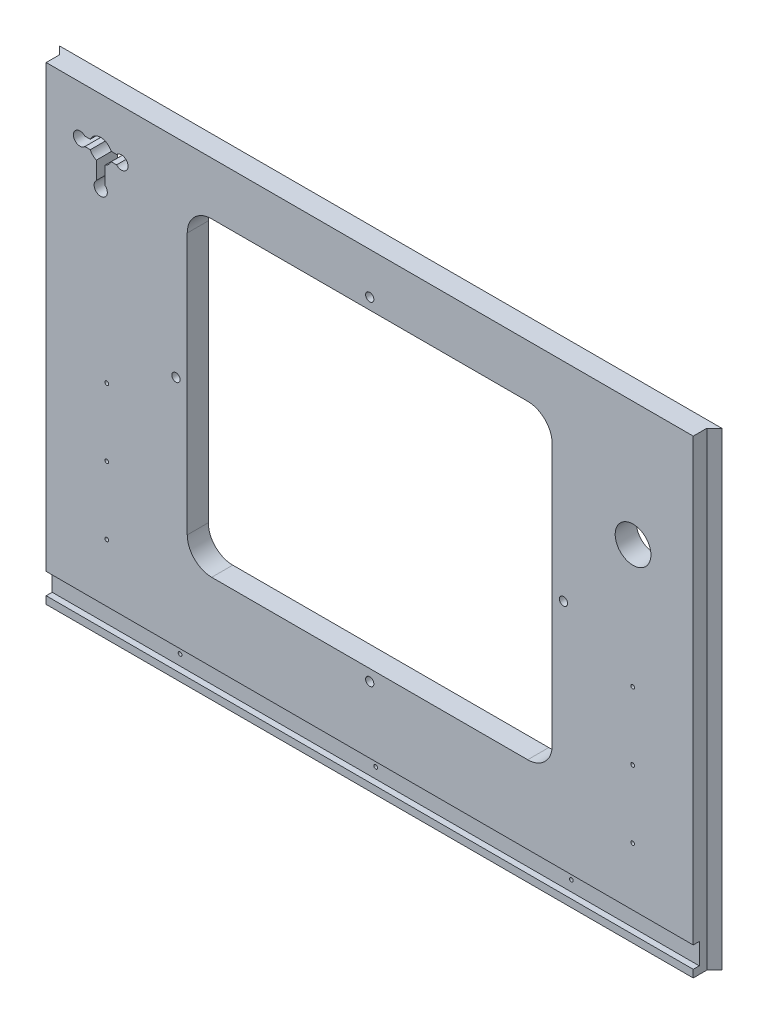
SolidWorks part; units mm, degrees
material "Pine"
ref_plane "Front Plane" through (0, 0, 0) normal (0, 0, 1) x (1, 0, 0)
ref_plane "Top Plane" through (0, 0, 0) normal (0, 1, 0) x (1, 0, 0)
ref_plane "Right Plane" through (0, 0, 0) normal (1, 0, 0) x (0, 0, -1)
sketch "Sketch1" plane through (0, 0, 0) normal (0, 0, 1) x (1, 0, 0)
  line L0 (8932.6508, -5243.5125) -> (10226.1458, -5243.5125)
  line L1 (9086.3208, -4722.0918) -> (10222.9708, -4853.7812)
  line L2 (8914.8708, -6342.0625) -> (10197.5708, -6342.0625)
  line L3 (8914.8708, -5808.6625) -> (10197.5708, -5808.6625)
  line L4 (8919.6333, -5253.0375) -> (10218.2083, -5253.0375)
  line L5 (9134.2633, -4656.1375) -> (9134.2633, -4638.3575)
  line L6 (9091.0833, -4638.3575) -> (9134.2633, -4638.3575)
  line L7 (9091.0833, -4567.2375) -> (9091.0833, -4638.3575)
  line L8 (9134.2633, -4656.1375) -> (9581.3033, -4656.1375)
  line L9 (9091.0833, -4567.2375) -> (9624.4833, -4567.2375)
  line L10 (9581.3033, -4656.1375) -> (9581.3033, -4638.3575)
  line L11 (9581.3033, -4638.3575) -> (9624.4833, -4638.3575)
  line L12 (9624.4833, -4567.2375) -> (9624.4833, -4638.3575)
  line L13 (8932.6508, -5225.7325) -> (9344.9775, -5225.7325)
  line L14 (8932.6508, -5256.2125) -> (8932.6508, -5243.5125)
  line L15 (8911.6958, -5256.2125) -> (8932.6508, -5256.2125)
  line L16 (8914.8708, -4722.0918) -> (9086.3208, -4722.0918)
  line L17 (8911.6958, -4715.5913) -> (8932.6508, -4715.5913)
  line L18 (8914.8708, -6342.0625) -> (8914.8708, -5808.6625)
  line L19 (12082.9917, -4722.0918) -> (10946.3417, -4853.7812)
  line L20 (12236.6617, -5243.5125) -> (10943.1667, -5243.5125)
  line L21 (10951.1042, -5253.0375) -> (12249.6792, -5253.0375)
  line L22 (10838.3917, -5656.2625) -> (11308.2917, -5656.2625)
  line L23 (10838.3917, -5719.7625) -> (11308.2917, -5719.7625)
  line L24 (10838.3917, -5742.5368) -> (11308.2917, -5742.5368)
  line L25 (10806.6417, -6342.0625) -> (11340.0417, -6342.0625)
  line L26 (10803.4667, -6335.7125) -> (11343.2167, -6335.7125)
  line L27 (10803.4667, -6317.9325) -> (11343.2167, -6317.9325)
  line L28 (10943.1667, -5225.7325) -> (11376.4483, -5225.7325)
  line L29 (11506.7292, -4754.5625) -> (10806.6417, -4827.5875)
  line L30 (11506.7292, -4567.2375) -> (11506.7292, -4754.5625)
  line L31 (10806.6417, -4567.2375) -> (10806.6417, -4827.5875)
  line L32 (10806.6417, -4567.2375) -> (11506.7292, -4567.2375)
  line L33 (10235.6708, -6329.3625) -> (10245.1958, -6329.3625)
  line L34 (10245.1958, -6329.3625) -> (10254.7208, -6278.5625)
  line L35 (10302.3458, -6329.3625) -> (10311.8708, -6278.5625)
  line L36 (10302.3458, -6329.3625) -> (10292.8208, -6329.3625)
  line L37 (10245.1958, -5821.3625) -> (10254.7208, -5872.1625)
  line L38 (10235.6708, -5821.3625) -> (10245.1958, -5821.3625)
  line L39 (10292.8208, -5821.3625) -> (10302.3458, -5821.3625)
  line L40 (10302.3458, -5821.3625) -> (10311.8708, -5872.1625)
  line L41 (10235.6708, -5821.3625) -> (10235.6708, -6329.3625)
  line L42 (10254.7208, -5872.1625) -> (10254.7208, -6278.5625)
  line L43 (10311.8708, -5872.1625) -> (10311.8708, -6278.5625)
  line L44 (10292.8208, -5821.3625) -> (10292.8208, -6329.3625)
  line L45 (8932.6508, -5225.7325) -> (8932.6508, -4715.5913)
  line L46 (8911.6958, -4715.5913) -> (8911.6958, -5256.2125)
  line L47 (8914.8708, -5248.275) -> (8914.8708, -4722.0918)
  line L48 (8919.6333, -5253.0375) -> (8914.8708, -5248.275)
  line L49 (8914.8708, -5145.0875) -> (8937.426, -5145.0875)
  line L50 (8914.8708, -5202.2375) -> (8937.426, -5202.2375)
  line L51 (10838.3917, -5656.2625) -> (10838.3917, -5719.7625)
  line L52 (10832.0417, -5736.1868) -> (10856.1717, -5736.1868)
  line L53 (10806.6417, -6342.0625) -> (10806.6417, -5818.7368)
  line L54 (10832.0417, -5649.9125) -> (10856.1717, -5649.9125)
  line L55 (10832.0417, -5726.1125) -> (10856.1717, -5726.1125)
  line L56 (10806.6417, -5818.7368) -> (10833.9015, -5818.7368)
  line L57 (10832.0417, -5806.0442) -> (10851.6815, -5806.0442)
  line L58 (10856.1717, -5801.5541) -> (10856.1717, -5736.1868)
  line L59 (10838.3917, -5814.2467) -> (10838.3917, -5742.5368)
  line L60 (10832.0417, -5806.0442) -> (10832.0417, -5736.1868)
  line L61 (10803.4667, -6317.9325) -> (10803.4667, -6335.7125)
  line L62 (10197.5708, -5808.6625) -> (10197.5708, -6342.0625)
  line L63 (9762.3842, -6348.4125) -> (9762.3842, -5802.3125)
  line L64 (9780.1642, -6348.4125) -> (9762.3842, -6348.4125)
  line L65 (9780.1642, -5802.3125) -> (9780.1642, -6348.4125)
  line L66 (9762.3842, -5802.3125) -> (9780.1642, -5802.3125)
  line L67 (9332.2775, -6348.4125) -> (9332.2775, -5802.3125)
  line L68 (9332.2775, -6348.4125) -> (9350.0575, -6348.4125)
  line L69 (9350.0575, -5802.3125) -> (9350.0575, -6348.4125)
  line L70 (9332.2775, -5802.3125) -> (9350.0575, -5802.3125)
  line L71 (9993.8374, -6061.075) -> (9993.8374, -6045.2418)
  line L72 (9998.5999, -6065.8375) -> (10014.4331, -6065.8375)
  line L73 (9998.5999, -6084.8875) -> (10014.4331, -6084.8875)
  line L74 (9993.8374, -6105.4832) -> (9993.8374, -6089.65)
  line L75 (9974.7874, -6105.4832) -> (9974.7874, -6089.65)
  line L76 (9954.1917, -6084.8875) -> (9970.0249, -6084.8875)
  line L77 (9974.7874, -6061.075) -> (9974.7874, -6045.2418)
  line L78 (9954.1917, -6065.8375) -> (9970.0249, -6065.8375)
  line L79 (10793.9417, -6237.2875) -> (10816.4969, -6237.2875)
  line L80 (10793.9417, -6294.4375) -> (10816.4969, -6294.4375)
  line L81 (10856.1717, -5649.9125) -> (10856.1717, -5726.1125)
  line L82 (10832.0417, -5726.1125) -> (10832.0417, -5649.9125)
  line L83 (10226.1458, -5225.7325) -> (10226.1458, -5243.5125)
  line L84 (10205.1908, -5257.8) -> (10205.1908, -4844.2499)
  line L85 (10230.9083, -4844.2499) -> (10230.9083, -5257.8)
  line L86 (10205.1908, -5257.8) -> (10230.9083, -5257.8)
  line L87 (10205.1908, -4844.2499) -> (10230.9083, -4844.2499)
  line L88 (10946.3417, -5176.8375) -> (10968.8969, -5176.8375)
  line L89 (9349.4676, -5141.9125) -> (9358.2674, -5141.9125)
  line L90 (10946.3417, -5119.6875) -> (10968.8969, -5119.6875)
  line L91 (9929.011, -4660.9635) -> (10066.0807, -4660.9635)
  line L92 (9929.011, -4678.7435) -> (10066.0807, -4678.7435)
  line L93 (10943.1667, -5225.7325) -> (10943.1667, -5243.5125)
  line L94 (10946.3417, -5248.275) -> (10951.1042, -5253.0375)
  line L95 (10946.3417, -5257.8063) -> (10946.3417, -4849.0188)
  line L96 (10964.1217, -5257.8) -> (10964.1217, -4844.2499)
  line L97 (10938.4042, -4844.2499) -> (10938.4042, -5257.8)
  line L98 (10938.4042, -5257.8) -> (10964.1217, -5257.8)
  line L99 (10964.1217, -4844.2499) -> (10938.4042, -4844.2499)
  line L100 (10344.8908, -4560.8875) -> (10369.0208, -4560.8875)
  line L101 (10344.8908, -4560.8875) -> (10369.0208, -4560.8875)
  line L102 (10800.2917, -4560.8875) -> (10824.4217, -4560.8875)
  line L103 (10200.4156, -5119.6875) -> (10222.9708, -5119.6875)
  line L104 (10200.4156, -5176.8375) -> (10222.9708, -5176.8375)
  line L105 (9344.9775, -5146.4026) -> (9344.9775, -5225.7325)
  line L106 (10344.8908, -4560.8875) -> (10344.8908, -4833.9375)
  line L107 (9792.8642, -5225.7325) -> (9792.8642, -5146.4026)
  line L108 (9362.7575, -5225.7325) -> (9775.0842, -5225.7325)
  line L109 (9680.3633, -4761.8396) -> (9680.3633, -4559.9604)
  line L110 (9656.2333, -4559.9604) -> (9680.3633, -4559.9604)
  line L111 (9656.2333, -4761.8396) -> (9680.3633, -4761.8396)
  line L112 (9656.2333, -4761.8396) -> (9656.2333, -4559.9604)
  line L113 (9779.5743, -5141.9125) -> (9788.374, -5141.9125)
  line L114 (10070.5708, -4665.4536) -> (10070.5708, -4674.2534)
  line L115 (9924.5208, -4674.2534) -> (9924.5208, -4665.4536)
  line L116 (12127.4417, -6188.3925) -> (12205.5015, -6188.3925)
  line L117 (12209.9917, -6170.6125) -> (12209.9917, -6183.9024)
  line L118 (9792.8642, -5225.7325) -> (10226.1458, -5225.7325)
  line L119 (9662.5833, -4754.5625) -> (10362.6708, -4827.5875)
  line L120 (9662.5833, -4567.2375) -> (9662.5833, -4754.5625)
  line L121 (10362.6708, -4567.2375) -> (10362.6708, -4827.5875)
  line L122 (9662.5833, -4567.2375) -> (10362.6708, -4567.2375)
  line L123 (10824.4217, -4833.9375) -> (10800.2917, -4833.9375)
  line L124 (10800.2917, -4833.9375) -> (10800.2917, -4560.8875)
  line L125 (10824.4217, -4560.8875) -> (10824.4217, -4833.9375)
  line L126 (10344.8908, -4833.9375) -> (10369.0208, -4833.9375)
  line L127 (10369.0208, -4833.9375) -> (10369.0208, -4560.8875)
  line L128 (10222.9708, -5248.275) -> (10218.2083, -5253.0375)
  line L129 (10222.9708, -5257.8063) -> (10222.9708, -4849.0188)
  line L130 (11734.6544, -5701.375) -> (11739.2301, -5701.375)
  line L131 (9362.7575, -5225.7325) -> (9362.7575, -5146.4026)
  line L132 (9775.0842, -5146.4026) -> (9775.0842, -5225.7325)
  line L133 (11761.3864, -5701.375) -> (11756.8282, -5701.375)
  line L134 (11734.6544, -5693.755) -> (11739.2301, -5693.755)
  line L135 (11761.4039, -5693.755) -> (11756.8282, -5693.755)
  line L136 (11734.6544, -5701.375) -> (11739.2301, -5701.375)
  line L137 (11744.3462, -5721.3024) -> (11744.3462, -5706.4179)
  line L138 (11751.7122, -5721.3024) -> (11751.7122, -5706.4179)
  line L139 (11740.0917, -6170.6125) -> (11740.0917, -6183.9024)
  line L140 (11689.2917, -6188.3925) -> (11822.6417, -6188.3925)
  line L141 (11689.2917, -6348.4093) -> (11689.2917, -6164.2657)
  line L142 (11689.2917, -6164.2657) -> (11746.4417, -6164.2657)
  line L143 (11746.4417, -6164.2657) -> (11746.4417, -6188.3925)
  line L144 (11689.2917, -6164.2657) -> (11746.4417, -6164.2657)
  line L145 (11340.0417, -5818.7368) -> (11340.0417, -6342.0625)
  line L146 (11290.5117, -5726.1125) -> (11314.6417, -5726.1125)
  line L147 (11290.5117, -5649.9125) -> (11290.5117, -5726.1125)
  line L148 (11340.0417, -5818.7368) -> (11312.7818, -5818.7368)
  line L149 (11314.6417, -5806.0442) -> (11295.0018, -5806.0442)
  line L150 (11290.5117, -5801.5541) -> (11290.5117, -5736.1868)
  line L151 (11308.2917, -5814.2467) -> (11308.2917, -5742.5368)
  line L152 (11314.6417, -5806.0442) -> (11314.6417, -5736.1868)
  line L153 (11290.5117, -5736.1868) -> (11314.6417, -5736.1868)
  line L154 (11848.0417, -6267.1325) -> (11962.3417, -6267.1325)
  line L155 (11962.3417, -6267.1325) -> (11962.3417, -6203.6325)
  line L156 (11343.2167, -6317.9325) -> (11343.2167, -6335.7125)
  line L157 (11365.4417, -5656.2625) -> (11365.4417, -5719.7625)
  line L158 (11365.4417, -5656.2625) -> (11479.7417, -5656.2625)
  line L159 (11778.1917, -6071.3937) -> (11802.3217, -6071.3937)
  line L160 (11314.6417, -5726.1125) -> (11314.6417, -5649.9125)
  line L161 (11314.6417, -5649.9125) -> (11290.5117, -5649.9125)
  line L162 (11308.2917, -5719.7625) -> (11308.2917, -5656.2625)
  line L163 (11689.2917, -6348.4093) -> (11713.4217, -6348.4093)
  line L164 (12203.6417, -6164.2657) -> (12260.7917, -6164.2657)
  line L165 (11713.4217, -6348.4093) -> (11713.4217, -6164.2657)
  line L166 (11695.6417, -6342.0625) -> (11695.6417, -6170.6125)
  line L167 (11695.6417, -6048.5337) -> (11699.4517, -6052.3437)
  line L168 (11822.6417, -6292.5325) -> (11822.6417, -6188.3925)
  line L169 (11695.6417, -6342.0625) -> (11695.6417, -6170.6125)
  line L170 (11848.0417, -6203.6325) -> (11962.3417, -6203.6325)
  line L171 (11848.0417, -6203.6325) -> (11848.0417, -6267.1325)
  line L172 (11987.7417, -6267.1325) -> (11987.7417, -6203.6325)
  line L173 (11784.5417, -6077.7437) -> (11784.5417, -6141.2438)
  line L174 (11517.8417, -5656.2625) -> (11632.1417, -5656.2625)
  line L175 (11632.1417, -5656.2625) -> (11632.1417, -5719.7625)
  line L176 (11632.1417, -5719.7625) -> (11517.8417, -5719.7625)
  line L177 (11517.8417, -5719.7625) -> (11517.8417, -5656.2625)
  line L178 (11692.4667, -6028.2137) -> (11692.4667, -6045.9937)
  line L179 (11695.6417, -5979.3188) -> (11718.1969, -5979.3188)
  line L180 (11695.6417, -5922.1687) -> (11718.1969, -5922.1687)
  line L181 (11821.0415, -5722.9375) -> (11821.0415, -5943.6)
  line L182 (11687.7042, -5651.5) -> (11701.9917, -5651.5)
  line L183 (11687.7042, -5651.5) -> (11687.7042, -6055.5251)
  line L184 (11687.7042, -6055.5251) -> (11701.9917, -6055.5251)
  line L185 (11701.9917, -6055.5251) -> (11701.9917, -5651.5)
  line L186 (11695.6417, -6055.2013) -> (11695.6417, -5649.595)
  line L187 (11695.6417, -5656.2625) -> (11695.6417, -6048.5337)
  line L188 (11695.6417, -6170.6125) -> (11740.0917, -6170.6125)
  line L189 (12203.6417, -6164.2657) -> (12203.6417, -6188.3925)
  line L190 (12254.4417, -6342.0625) -> (12254.4417, -6170.6125)
  line L191 (12129.0419, -5943.6) -> (12129.0419, -5722.9375)
  line L192 (12254.4417, -6048.5337) -> (12250.6317, -6052.3437)
  line L193 (12257.6167, -6045.9937) -> (12257.6167, -6028.2137)
  line L194 (12248.0917, -5651.5) -> (12262.3792, -5651.5)
  line L195 (12262.3792, -5651.5) -> (12262.3792, -6055.5251)
  line L196 (12262.3792, -6055.5251) -> (12248.0917, -6055.5251)
  line L197 (12248.0917, -6055.5251) -> (12248.0917, -5651.5)
  line L198 (12254.4417, -6141.2438) -> (12254.4417, -6077.7437)
  line L199 (12236.6617, -6164.2657) -> (12260.7917, -6164.2657)
  line L200 (12102.0417, -6267.1325) -> (11987.7417, -6267.1325)
  line L201 (11330.1865, -6237.2875) -> (11352.7417, -6237.2875)
  line L202 (11330.1865, -6294.4375) -> (11352.7417, -6294.4375)
  line L203 (11474.6617, -5851.8425) -> (11492.4417, -5851.8425)
  line L204 (11474.6617, -5808.6625) -> (11474.6617, -5851.8425)
  line L205 (11403.5417, -5808.6625) -> (11474.6617, -5808.6625)
  line L206 (11492.4417, -5851.8425) -> (11492.4417, -6298.8825)
  line L207 (11403.5417, -6342.0625) -> (11403.5417, -5808.6625)
  line L208 (11474.6617, -6298.8825) -> (11492.4417, -6298.8825)
  line L209 (11474.6617, -6342.0625) -> (11474.6617, -6298.8825)
  line L210 (11403.5417, -6342.0625) -> (11474.6617, -6342.0625)
  line L211 (11619.4417, -5851.8425) -> (11601.6617, -5851.8425)
  line L212 (11601.6617, -5808.6625) -> (11601.6617, -5851.8425)
  line L213 (11530.5417, -5808.6625) -> (11601.6617, -5808.6625)
  line L214 (11619.4417, -5851.8425) -> (11619.4417, -6298.8825)
  line L215 (11530.5417, -6342.0625) -> (11530.5417, -5808.6625)
  line L216 (11619.4417, -6298.8825) -> (11601.6617, -6298.8825)
  line L217 (11601.6617, -6342.0625) -> (11601.6617, -6298.8825)
  line L218 (11530.5417, -6342.0625) -> (11601.6617, -6342.0625)
  line L219 (11479.7417, -5719.7625) -> (11479.7417, -5656.2625)
  line L220 (11365.4417, -5719.7625) -> (11479.7417, -5719.7625)
  line L221 (11778.1917, -6147.5937) -> (11802.3217, -6147.5937)
  line L222 (11802.3217, -6071.3937) -> (11802.3217, -6147.5937)
  line L223 (11778.1917, -6147.5937) -> (11778.1917, -6071.3937)
  line L224 (12254.4417, -5922.1687) -> (12231.8865, -5922.1687)
  line L225 (12254.4417, -5979.3188) -> (12231.8865, -5979.3188)
  line L226 (12254.4417, -6055.2013) -> (12254.4417, -5649.595)
  line L227 (12254.4417, -6048.5337) -> (12254.4417, -5656.2625)
  line L228 (11841.6917, -5702.2873) -> (12108.3917, -5702.2873)
  line L229 (11822.6417, -6292.5325) -> (12127.4417, -6292.5325)
  line L230 (12127.4417, -6292.5325) -> (12127.4417, -6188.3925)
  line L231 (12254.4417, -6170.6125) -> (12209.9917, -6170.6125)
  line L232 (11695.6417, -6342.0625) -> (12254.4417, -6342.0625)
  line L233 (12236.6617, -6348.4093) -> (12260.7917, -6348.4093)
  line L234 (12260.7917, -6348.4093) -> (12260.7917, -6164.2657)
  line L235 (12236.6617, -6348.4093) -> (12236.6617, -6164.2657)
  line L236 (12102.0417, -6203.6325) -> (12102.0417, -6267.1325)
  line L237 (11987.7417, -6203.6325) -> (12102.0417, -6203.6325)
  line L238 (12236.6617, -6147.5937) -> (12236.6617, -6071.3937)
  line L239 (12203.6417, -6188.3925) -> (12260.7917, -6188.3925)
  line L240 (11098.7417, -4665.4536) -> (11098.7417, -4674.2534)
  line L241 (11394.2283, -5146.4026) -> (11394.2283, -5225.7325)
  line L242 (11376.4483, -5225.7325) -> (11376.4483, -5146.4026)
  line L243 (11394.2283, -5225.7325) -> (11806.555, -5225.7325)
  line L244 (11841.6917, -5964.2502) -> (12108.3917, -5964.2502)
  line L245 (12236.6617, -6147.5937) -> (12260.7917, -6147.5937)
  line L246 (12236.6617, -5256.2125) -> (12236.6617, -5243.5125)
  line L247 (12260.7917, -6147.5937) -> (12260.7917, -6071.3937)
  line L248 (12260.7917, -6071.3937) -> (12236.6617, -6071.3937)
  line L249 (12254.4417, -6077.7437) -> (11784.5417, -6077.7437)
  line L250 (11784.5417, -6141.2438) -> (12254.4417, -6141.2438)
  line L252 (12254.4417, -5656.2625) -> (11695.6417, -5656.2625)
  line L253 (11699.4517, -6052.3437) -> (12250.6317, -6052.3437)
  line L254 (11692.4667, -6045.9937) -> (12257.6167, -6045.9937)
  line L255 (11692.4667, -6028.2137) -> (12257.6167, -6028.2137)
  line L256 (11824.335, -5146.4026) -> (11824.335, -5225.7325)
  line L257 (11811.0451, -5141.9125) -> (11819.8449, -5141.9125)
  line L258 (11244.7917, -4674.2534) -> (11244.7917, -4665.4536)
  line L259 (11806.555, -5225.7325) -> (11806.555, -5146.4026)
  line L260 (11488.9492, -4761.8396) -> (11488.9492, -4559.9604)
  line L261 (11488.9492, -4559.9604) -> (11513.0792, -4559.9604)
  line L262 (11488.9492, -4761.8396) -> (11513.0792, -4761.8396)
  line L263 (11513.0792, -4761.8396) -> (11513.0792, -4559.9604)
  line L264 (11240.3015, -4660.9635) -> (11103.2318, -4660.9635)
  line L265 (11103.2318, -4678.7435) -> (11240.3015, -4678.7435)
  line L266 (12236.6617, -5225.7325) -> (12236.6617, -4715.5913)
  line L267 (12257.6167, -4715.5913) -> (12257.6167, -5256.2125)
  line L268 (12254.4417, -5248.275) -> (12254.4417, -4722.0918)
  line L269 (12236.6617, -5225.7325) -> (11824.335, -5225.7325)
  line L270 (12035.0492, -4656.1375) -> (12035.0492, -4638.3575)
  line L271 (12078.2292, -4638.3575) -> (12035.0492, -4638.3575)
  line L272 (12078.2292, -4567.2375) -> (12078.2292, -4638.3575)
  line L273 (12035.0492, -4656.1375) -> (11588.0092, -4656.1375)
  line L274 (11544.8292, -4567.2375) -> (12078.2292, -4567.2375)
  line L275 (11588.0092, -4656.1375) -> (11588.0092, -4638.3575)
  line L276 (11544.8292, -4638.3575) -> (11588.0092, -4638.3575)
  line L277 (11544.8292, -4567.2375) -> (11544.8292, -4638.3575)
  line L278 (12249.6792, -5253.0375) -> (12254.4417, -5248.275)
  line L280 (12257.6167, -5256.2125) -> (12236.6617, -5256.2125)
  line L281 (12231.8865, -5145.0875) -> (12254.4417, -5145.0875)
  line L282 (12231.8865, -5202.2375) -> (12254.4417, -5202.2375)
  line L283 (12236.6617, -4715.5913) -> (12257.6167, -4715.5913)
  line L284 (12082.9917, -4722.0918) -> (12254.4417, -4722.0918)
  line L285 (11380.9385, -5141.9125) -> (11389.7382, -5141.9125)
  circle A0 centre (8923.7608, -4778.9042) radius 1.5875
  circle A1 centre (9062.6598, -4736.3765) radius 2.3685
  circle A2 centre (9051.3958, -6281.7375) radius 22.225
  circle A3 centre (9083.1458, -6249.9875) radius 1.5875
  circle A4 centre (9083.1458, -6313.4875) radius 1.5875
  circle A5 centre (9019.6458, -6249.9875) radius 1.5875
  circle A6 centre (9019.6458, -6313.4875) radius 1.5875
  circle A7 centre (8972.3383, -5202.2375) radius 1.5875
  circle A8 centre (8923.7608, -5015.9708) radius 1.5875
  circle A9 centre (8923.7608, -5134.5042) radius 1.5875
  circle A10 centre (9054.5708, -5234.6225) radius 1.5875
  circle A11 centre (8923.7608, -4897.4375) radius 1.5875
  circle A12 centre (8972.3383, -5087.9375) radius 1.5875
  circle A13 centre (8972.3383, -5145.0875) radius 1.5875
  circle A14 centre (10847.2817, -5668.9625) radius 1.5875
  circle A15 centre (10847.2817, -5707.0625) radius 1.5875
  circle A16 centre (10847.2817, -5755.2368) radius 1.5875
  circle A17 centre (10851.4092, -6237.2875) radius 1.5875
  circle A18 centre (10851.4092, -6294.4375) radius 1.5875
  circle A19 centre (10847.2817, -5793.3442) radius 1.5875
  arc A20 (10833.9015, -5818.7368) -> (10838.3917, -5814.2467) centre (10836.1466, -5816.4918) ccw
  arc A21 (10851.6815, -5806.0442) -> (10856.1717, -5801.5541) centre (10853.9266, -5803.7992) ccw
  circle A22 centre (10882.8417, -6040.4375) radius 1.5875
  circle A23 centre (10882.8417, -6218.2375) radius 1.5875
  circle A24 centre (10882.8417, -5862.6375) radius 1.5875
  circle A25 centre (10908.2417, -6326.8225) radius 1.5875
  circle A26 centre (10908.2417, -6326.8225) radius 1.5875
  circle A27 centre (10851.4092, -6180.1375) radius 1.5875
  circle A28 centre (10815.5317, -4783.4231) radius 1.5875
  circle A29 centre (10815.5317, -4696.9488) radius 1.5875
  circle A30 centre (10815.5317, -4610.4746) radius 1.5875
  circle A31 centre (10979.1323, -4867.0082) radius 2.3685
  circle A32 centre (10190.1802, -4867.0082) radius 2.3685
  circle A33 centre (10955.2317, -4929.9812) radius 1.5875
  circle A34 centre (10955.2317, -5031.5812) radius 1.5875
  circle A35 centre (10214.0808, -4929.9812) radius 1.5875
  circle A36 centre (10214.0808, -5031.5812) radius 1.5875
  circle A37 centre (9341.1675, -6265.8625) radius 1.5875
  circle A38 centre (9771.2742, -5884.8625) radius 1.5875
  circle A39 centre (9771.2742, -6138.8625) radius 1.5875
  circle A40 centre (9771.2742, -6011.8625) radius 1.5875
  arc A41 (10036.2287, -6113.8083) -> (10051.3426, -6111.6033) centre (10042.9639, -6107.0732) ccw
  arc A42 (10051.3426, -6111.6033) -> (10051.3426, -6039.1217) centre (9984.3124, -6075.3625) ccw
  arc A43 (10051.3426, -6039.1217) -> (10036.2287, -6036.9167) centre (10042.9639, -6043.6518) ccw
  arc A44 (10034.5851, -6102.5431) -> (10034.5851, -6048.1819) centre (9984.3124, -6075.3625) ccw
  arc A45 (10034.5851, -6102.5431) -> (10036.2287, -6113.8083) centre (10042.9639, -6107.0732) ccw
  arc A46 (10036.2287, -6036.9167) -> (10034.5851, -6048.1819) centre (10042.9639, -6043.6518) ccw
  arc A47 (9945.8666, -6127.2787) -> (9948.0717, -6142.3927) centre (9952.6018, -6134.0139) ccw
  arc A48 (9948.0717, -6142.3927) -> (10020.5532, -6142.3927) centre (9984.3124, -6075.3625) ccw
  arc A49 (10020.5532, -6142.3927) -> (10022.7583, -6127.2787) centre (10016.0231, -6134.0139) ccw
  arc A50 (9957.1319, -6125.6352) -> (10011.493, -6125.6352) centre (9984.3124, -6075.3625) ccw
  arc A51 (9957.1319, -6125.6352) -> (9945.8666, -6127.2787) centre (9952.6018, -6134.0139) ccw
  arc A52 (10022.7583, -6127.2787) -> (10011.493, -6125.6352) centre (10016.0231, -6134.0139) ccw
  arc A53 (9932.3962, -6036.9167) -> (9917.2822, -6039.1217) centre (9925.661, -6043.6518) ccw
  arc A54 (9917.2822, -6039.1217) -> (9917.2822, -6111.6033) centre (9984.3124, -6075.3625) ccw
  arc A55 (9917.2822, -6111.6033) -> (9932.3962, -6113.8083) centre (9925.661, -6107.0732) ccw
  arc A56 (9934.0398, -6048.1819) -> (9934.0398, -6102.5431) centre (9984.3124, -6075.3625) ccw
  arc A57 (9934.0398, -6048.1819) -> (9932.3962, -6036.9167) centre (9925.661, -6043.6518) ccw
  arc A58 (9932.3962, -6113.8083) -> (9934.0398, -6102.5431) centre (9925.661, -6107.0732) ccw
  arc A59 (9945.8666, -6023.4463) -> (9957.1319, -6025.0898) centre (9952.6018, -6016.7111) ccw
  arc A60 (10011.493, -6025.0898) -> (10022.7583, -6023.4463) centre (10016.0231, -6016.7111) ccw
  arc A61 (10011.493, -6025.0898) -> (9957.1319, -6025.0898) centre (9984.3124, -6075.3625) ccw
  arc A62 (9948.0717, -6008.3323) -> (9945.8666, -6023.4463) centre (9952.6018, -6016.7111) ccw
  arc A63 (10020.5532, -6008.3323) -> (9948.0717, -6008.3323) centre (9984.3124, -6075.3625) ccw
  arc A64 (10022.7583, -6023.4463) -> (10020.5532, -6008.3323) centre (10016.0231, -6016.7111) ccw
  arc A65 (10005.0943, -6187.7574) -> (10096.7073, -6096.1443) centre (9984.3124, -6075.3625) ccw
  arc A66 (9993.8374, -6178.3911) -> (10005.0943, -6187.7574) centre (10003.3624, -6178.3911) ccw
  arc A67 (10001.6306, -6169.0249) -> (10077.9748, -6092.6807) centre (9984.3124, -6075.3625) ccw
  arc A68 (10087.3411, -6084.8875) -> (10077.9748, -6092.6807) centre (10087.3411, -6094.4125) ccw
  arc A69 (10001.6306, -6169.0249) -> (9993.8374, -6178.3911) centre (10003.3624, -6178.3911) ccw
  arc A70 (9963.5306, -6187.7574) -> (9974.7874, -6178.3911) centre (9965.2624, -6178.3911) ccw
  arc A71 (9871.9176, -6096.1443) -> (9963.5306, -6187.7574) centre (9984.3124, -6075.3625) ccw
  arc A72 (9881.2838, -6084.8875) -> (9871.9176, -6096.1443) centre (9881.2838, -6094.4125) ccw
  arc A73 (9890.65, -6092.6807) -> (9966.9943, -6169.0249) centre (9984.3124, -6075.3625) ccw
  arc A74 (9974.7874, -6178.3911) -> (9966.9943, -6169.0249) centre (9965.2624, -6178.3911) ccw
  arc A75 (9890.65, -6092.6807) -> (9881.2838, -6084.8875) centre (9881.2838, -6094.4125) ccw
  arc A76 (9871.9176, -6054.5807) -> (9881.2838, -6065.8375) centre (9881.2838, -6056.3125) ccw
  arc A77 (9963.5306, -5962.9676) -> (9871.9176, -6054.5807) centre (9984.3124, -6075.3625) ccw
  arc A78 (9974.7874, -5972.3339) -> (9963.5306, -5962.9676) centre (9965.2624, -5972.3339) ccw
  arc A79 (9966.9943, -5981.7001) -> (9890.65, -6058.0443) centre (9984.3124, -6075.3625) ccw
  arc A80 (9881.2838, -6065.8375) -> (9890.65, -6058.0443) centre (9881.2838, -6056.3125) ccw
  arc A81 (9966.9943, -5981.7001) -> (9974.7874, -5972.3339) centre (9965.2624, -5972.3339) ccw
  arc A82 (10077.9748, -6058.0443) -> (10087.3411, -6065.8375) centre (10087.3411, -6056.3125) ccw
  arc A83 (9993.8374, -5972.3339) -> (10001.6306, -5981.7001) centre (10003.3624, -5972.3339) ccw
  arc A84 (10077.9748, -6058.0443) -> (10001.6306, -5981.7001) centre (9984.3124, -6075.3625) ccw
  arc A85 (10087.3411, -6065.8375) -> (10096.7073, -6054.5807) centre (10087.3411, -6056.3125) ccw
  arc A86 (10096.7073, -6054.5807) -> (10005.0943, -5962.9676) centre (9984.3124, -6075.3625) ccw
  arc A87 (10005.0943, -5962.9676) -> (9993.8374, -5972.3339) centre (10003.3624, -5972.3339) ccw
  arc A88 (10014.4331, -6065.8375) -> (10018.7361, -6059.0339) centre (10014.4331, -6061.075) ccw
  arc A89 (10018.7361, -6059.0339) -> (10000.641, -6040.9388) centre (9984.3124, -6075.3625) ccw
  arc A90 (10000.641, -6040.9388) -> (9993.8374, -6045.2418) centre (9998.5999, -6045.2418) ccw
  arc A91 (9993.8374, -6061.075) -> (9998.5999, -6065.8375) centre (9998.5999, -6061.075) ccw
  arc A92 (9993.8374, -6105.4832) -> (10000.641, -6109.7862) centre (9998.5999, -6105.4832) ccw
  arc A93 (10000.641, -6109.7862) -> (10018.7361, -6091.6911) centre (9984.3124, -6075.3625) ccw
  arc A94 (10018.7361, -6091.6911) -> (10014.4331, -6084.8875) centre (10014.4331, -6089.65) ccw
  arc A95 (9998.5999, -6084.8875) -> (9993.8374, -6089.65) centre (9998.5999, -6089.65) ccw
  arc A96 (9954.1917, -6084.8875) -> (9949.8888, -6091.6911) centre (9954.1917, -6089.65) ccw
  arc A97 (9949.8888, -6091.6911) -> (9967.9839, -6109.7862) centre (9984.3124, -6075.3625) ccw
  arc A98 (9967.9839, -6109.7862) -> (9974.7874, -6105.4832) centre (9970.0249, -6105.4832) ccw
  arc A99 (9974.7874, -6089.65) -> (9970.0249, -6084.8875) centre (9970.0249, -6089.65) ccw
  arc A100 (9970.0249, -6065.8375) -> (9974.7874, -6061.075) centre (9970.0249, -6061.075) ccw
  arc A101 (9949.8888, -6059.0339) -> (9954.1917, -6065.8375) centre (9954.1917, -6061.075) ccw
  arc A102 (9967.9839, -6040.9388) -> (9949.8888, -6059.0339) centre (9984.3124, -6075.3625) ccw
  arc A103 (9974.7874, -6045.2418) -> (9967.9839, -6040.9388) centre (9970.0249, -6045.2418) ccw
  arc A104 (10096.7073, -6096.1443) -> (10087.3411, -6084.8875) centre (10087.3411, -6094.4125) ccw
  circle A105 centre (9771.2742, -6265.8625) radius 1.5875
  circle A106 centre (9341.1675, -5884.8625) radius 1.5875
  circle A107 centre (9341.1675, -6138.8625) radius 1.5875
  circle A108 centre (9341.1675, -6011.8625) radius 1.5875
  circle A109 centre (11037.2315, -4887.5494) radius 15.0812
  arc A110 (9349.4676, -5141.9125) -> (9344.9775, -5146.4026) centre (9347.2226, -5144.1576) ccw
  arc A111 (9362.7575, -5146.4026) -> (9358.2674, -5141.9125) centre (9360.5124, -5144.1576) ccw
  circle A112 centre (9946.7458, -4669.8535) radius 1.5875
  arc A113 (9924.5208, -4674.2534) -> (9929.011, -4678.7435) centre (9926.7659, -4676.4984) ccw
  circle A114 centre (11003.8092, -5176.8375) radius 1.5875
  circle A115 centre (11003.8092, -5119.6875) radius 1.5875
  circle A116 centre (10353.7808, -4696.9488) radius 1.5875
  circle A117 centre (10353.7808, -4610.4746) radius 1.5875
  circle A118 centre (10353.7808, -4783.4231) radius 1.5875
  circle A119 centre (11003.8092, -5062.5375) radius 1.5875
  circle A120 centre (9353.8675, -5160.9625) radius 1.5875
  circle A121 centre (9638.7708, -5234.6225) radius 1.5875
  circle A122 centre (9671.4733, -4724.1144) radius 1.5875
  circle A123 centre (9671.4733, -4661.3637) radius 1.5875
  circle A124 centre (9671.4733, -4598.6129) radius 1.5875
  arc A125 (9792.8642, -5146.4026) -> (9788.374, -5141.9125) centre (9790.6191, -5144.1576) ccw
  arc A126 (9779.5743, -5141.9125) -> (9775.0842, -5146.4026) centre (9777.3292, -5144.1576) ccw
  circle A127 centre (10048.3458, -4669.8535) radius 1.5875
  arc A128 (10070.5708, -4665.4536) -> (10066.0807, -4660.9635) centre (10068.3258, -4663.2086) ccw
  arc A129 (10066.0807, -4678.7435) -> (10070.5708, -4674.2534) centre (10068.3258, -4676.4984) ccw
  circle A130 centre (9997.5458, -4669.8535) radius 1.5875
  arc A131 (9929.011, -4660.9635) -> (9924.5208, -4665.4536) centre (9926.7659, -4663.2086) ccw
  circle A132 centre (10132.081, -4887.5494) radius 15.0812
  circle A133 centre (10165.5033, -5176.8375) radius 1.5875
  circle A134 centre (10165.5033, -5119.6875) radius 1.5875
  circle A135 centre (9486.3708, -5234.6225) radius 1.5875
  circle A136 centre (10165.5033, -5062.5375) radius 1.5875
  circle A137 centre (9206.9708, -5234.6225) radius 1.5875
  circle A138 centre (10070.5708, -5234.6225) radius 1.5875
  circle A139 centre (9918.1708, -5234.6225) radius 1.5875
  circle A140 centre (9783.9742, -5160.9625) radius 1.5875
  circle A141 centre (9783.9742, -5193.9825) radius 1.5875
  circle A142 centre (9353.8675, -5193.9825) radius 1.5875
  circle A143 centre (11073.3417, -6326.8225) radius 1.5875
  circle A144 centre (11073.3417, -6326.8225) radius 1.5875
  circle A145 centre (11295.2742, -6180.1375) radius 1.5875
  circle A146 centre (11295.2742, -6294.4375) radius 1.5875
  circle A147 centre (11295.2742, -6237.2875) radius 1.5875
  circle A148 centre (11975.0417, -5692.775) radius 3.4925
  circle A149 centre (11263.8417, -5862.6375) radius 1.5875
  arc A150 (11739.2301, -5701.375) -> (11744.3462, -5706.4179) centre (11748.0292, -5697.565) ccw
  arc A151 (11751.7122, -5706.4179) -> (11756.8282, -5701.375) centre (11748.0292, -5697.565) ccw
  arc A152 (11744.3462, -5721.3024) -> (11751.7122, -5721.3024) centre (11748.0292, -5725.505) ccw
  arc A153 (11734.6544, -5693.755) -> (11724.9787, -5697.565) centre (11730.5667, -5697.565) ccw
  arc A154 (11756.8282, -5693.755) -> (11739.2301, -5693.755) centre (11748.0292, -5697.565) ccw
  arc A155 (11724.9787, -5697.565) -> (11734.6544, -5701.375) centre (11730.5667, -5697.565) ccw
  arc A156 (11761.3864, -5701.375) -> (11771.0797, -5697.565) centre (11765.4842, -5697.565) ccw
  arc A157 (11771.0797, -5697.565) -> (11761.4039, -5693.755) centre (11765.4917, -5697.565) ccw
  arc A158 (11740.0917, -6183.9024) -> (11744.5818, -6188.3925) centre (11742.3367, -6186.1474) ccw
  arc A159 (12205.5015, -6188.3925) -> (12209.9917, -6183.9024) centre (12207.7466, -6186.1474) ccw
  circle A160 centre (11299.4017, -5793.3442) radius 1.5875
  arc A161 (11308.2917, -5814.2467) -> (11312.7818, -5818.7368) centre (11310.5367, -5816.4918) ccw
  arc A162 (11290.5117, -5801.5541) -> (11295.0018, -5806.0442) centre (11292.7567, -5803.7992) ccw
  circle A163 centre (11704.5317, -6314.149) radius 1.5875
  circle A164 centre (11748.9817, -6208.7125) radius 1.5875
  circle A165 centre (11263.8417, -6218.2375) radius 1.5875
  circle A166 centre (11263.8417, -6040.4375) radius 1.5875
  circle A167 centre (11238.4417, -6326.8225) radius 1.5875
  circle A168 centre (11238.4417, -6326.8225) radius 1.5875
  circle A169 centre (11299.4017, -5668.9625) radius 1.5875
  circle A170 centre (11299.4017, -5707.0625) radius 1.5875
  circle A171 centre (11726.7567, -6179.5025) radius 1.5875
  circle A172 centre (11704.5317, -6199.3198) radius 1.5875
  circle A173 centre (11748.9817, -6272.2125) radius 1.5875
  circle A174 centre (11704.5317, -6256.7344) radius 1.5875
  circle A175 centre (11299.4017, -5755.2368) radius 1.5875
  circle A176 centre (11913.4467, -6301.4225) radius 1.5875
  circle A177 centre (11790.2567, -6301.4225) radius 1.5875
  circle A178 centre (11793.4317, -6128.5437) radius 1.5875
  circle A179 centre (11753.1092, -5865.0188) radius 1.5875
  circle A180 centre (11809.9417, -6037.1038) radius 1.5875
  circle A181 centre (11809.9417, -6037.1038) radius 1.5875
  circle A182 centre (11753.1092, -5922.1687) radius 1.5875
  circle A183 centre (11975.0417, -5973.7625) radius 3.4925
  circle A184 centre (11975.0417, -6037.1038) radius 1.5875
  circle A185 centre (11753.1092, -5979.3188) radius 1.5875
  circle A186 centre (11975.0417, -6037.1038) radius 1.5875
  arc A187 (11841.6917, -5702.2873) -> (11821.0415, -5722.9375) centre (11841.6917, -5722.9375) ccw
  circle A188 centre (11811.5292, -5833.2687) radius 3.4925
  arc A189 (11821.0415, -5943.6) -> (11841.6917, -5964.2502) centre (11841.6917, -5943.6) ccw
  circle A190 centre (12196.9742, -5865.0188) radius 1.5875
  arc A191 (12129.0419, -5722.9375) -> (12108.3917, -5702.2873) centre (12108.3917, -5722.9375) ccw
  circle A192 centre (12036.6367, -6301.4225) radius 1.5875
  circle A193 centre (12159.8267, -6301.4225) radius 1.5875
  circle A194 centre (12138.5542, -5833.2687) radius 3.4925
  circle A195 centre (12197.2917, -5761.0375) radius 15.0812
  circle A196 centre (11793.4317, -6090.4437) radius 1.5875
  circle A197 centre (12196.9742, -5922.1687) radius 1.5875
  arc A198 (12108.3917, -5964.2502) -> (12129.0419, -5943.6) centre (12108.3917, -5943.6) ccw
  circle A199 centre (12196.9742, -5979.3188) radius 1.5875
  circle A200 centre (12201.1017, -6272.2125) radius 1.5875
  circle A201 centre (12245.5517, -6314.149) radius 1.5875
  circle A202 centre (12245.5517, -6256.7344) radius 1.5875
  circle A203 centre (12201.1017, -6208.7125) radius 1.5875
  circle A204 centre (12223.3267, -6179.5025) radius 1.5875
  circle A205 centre (12245.5517, -6199.3198) radius 1.5875
  circle A206 centre (11171.7667, -4669.8535) radius 1.5875
  circle A207 centre (11222.5667, -4669.8535) radius 1.5875
  arc A208 (11240.3015, -4678.7435) -> (11244.7917, -4674.2534) centre (11242.5466, -4676.4984) ccw
  circle A209 centre (11385.3383, -5193.9825) radius 1.5875
  circle A210 centre (12106.6527, -4736.3765) radius 2.3685
  circle A211 centre (12140.1417, -6037.1038) radius 1.5875
  circle A212 centre (12140.1417, -6037.1038) radius 1.5875
  circle A213 centre (12245.5517, -6090.4437) radius 1.5875
  circle A214 centre (12245.5517, -6128.5437) radius 1.5875
  circle A215 centre (11385.3383, -5160.9625) radius 1.5875
  arc A216 (11824.335, -5146.4026) -> (11819.8449, -5141.9125) centre (11822.0899, -5144.1576) ccw
  arc A217 (11811.0451, -5141.9125) -> (11806.555, -5146.4026) centre (11808.8001, -5144.1576) ccw
  circle A218 centre (11815.445, -5193.9825) radius 1.5875
  circle A219 centre (11815.445, -5160.9625) radius 1.5875
  circle A220 centre (11530.5417, -5234.6225) radius 1.5875
  circle A221 centre (11962.3417, -5234.6225) radius 1.5875
  arc A222 (11244.7917, -4665.4536) -> (11240.3015, -4660.9635) centre (11242.5466, -4663.2086) ccw
  circle A223 centre (11682.9417, -5234.6225) radius 1.5875
  circle A224 centre (11497.8392, -4724.1144) radius 1.5875
  circle A225 centre (11497.8392, -4661.3637) radius 1.5875
  circle A226 centre (11497.8392, -4598.6129) radius 1.5875
  circle A227 centre (11120.9667, -4669.8535) radius 1.5875
  arc A228 (11103.2318, -4660.9635) -> (11098.7417, -4665.4536) centre (11100.9867, -4663.2086) ccw
  arc A229 (11098.7417, -4674.2534) -> (11103.2318, -4678.7435) centre (11100.9867, -4676.4984) ccw
  circle A230 centre (12196.9742, -5202.2375) radius 1.5875
  circle A231 centre (12245.5517, -5015.9708) radius 1.5875
  circle A232 centre (12245.5517, -5134.5042) radius 1.5875
  circle A233 centre (12114.7417, -5234.6225) radius 1.5875
  circle A234 centre (12245.5517, -4897.4375) radius 1.5875
  circle A235 centre (12245.5517, -4778.9042) radius 1.5875
  circle A236 centre (12196.9742, -5087.9375) radius 1.5875
  circle A237 centre (12196.9742, -5145.0875) radius 1.5875
  circle A238 centre (11098.7417, -5234.6225) radius 1.5875
  circle A239 centre (11251.1417, -5234.6225) radius 1.5875
  arc A240 (11380.9385, -5141.9125) -> (11376.4483, -5146.4026) centre (11378.6934, -5144.1576) ccw
  arc A241 (11394.2283, -5146.4026) -> (11389.7382, -5141.9125) centre (11391.9833, -5144.1576) ccw
sketch "Sketch2" plane through (0, 0, 0) normal (0, 0, 1) x (1, 0, 0)
  line L0 (11695.6417, -6055.2013) -> (11695.6417, -5649.595) construction
  line L1 (11695.6417, -6052.3437) -> (12254.4417, -6052.3437)
  line L3 (12254.4417, -6052.3437) -> (12254.4417, -5656.2625)
  line L4 (12254.4417, -5656.2625) -> (11695.6417, -5656.2625)
  line L5 (11695.6417, -5656.2625) -> (11695.6417, -6052.3437)
  point P1 (0, 0)
  point P2 (0, 0)
  dimension "D1" = 558.8
extrude "Extrude1" add sketch "Sketch2" against normal blind 17.78
sketch "Sketch3" plane through (0, 0, 0) normal (0, 0, 1) x (1, 0, 0)
  line L0 (11821.0415, -5700.6998) -> (12129.0419, -5700.6998)
  line L1 (12129.0419, -5700.6998) -> (12129.0419, -5962.6627)
  line L2 (12129.0419, -5962.6627) -> (11821.0415, -5962.6627)
  line L3 (11821.0415, -5962.6627) -> (11821.0415, -5700.6998)
  line L4 (11734.6544, -5693.755) -> (11739.2301, -5693.755)
  line L5 (11734.6544, -5701.375) -> (11739.2301, -5701.375)
  line L6 (11744.3462, -5706.4179) -> (11744.3462, -5721.3024)
  line L7 (11751.7122, -5706.4179) -> (11751.7122, -5721.3024)
  line L8 (11756.8282, -5701.375) -> (11761.3864, -5701.375)
  line L9 (11761.3864, -5693.755) -> (11756.8282, -5693.755)
  line L10 (11753.1092, -5865.0188) -> (11753.1092, -5922.1687) construction
  line L11 (11753.1092, -5922.1687) -> (11753.1092, -5979.3188) construction
  line L12 (11695.6417, -5656.2625) -> (11695.6417, -6052.3437) construction
  line L13 (12196.9742, -5865.0188) -> (12196.9742, -5922.1687) construction
  line L14 (12196.9742, -5922.1687) -> (12196.9742, -5979.3188) construction
  line L15 (12254.4417, -6052.3437) -> (12254.4417, -5656.2625) construction
  line L16 (11809.9417, -6037.1038) -> (11975.0417, -6037.1038) construction
  line L17 (11975.0417, -6037.1038) -> (12140.1417, -6037.1038) construction
  line L18 (11975.0417, -6037.1038) -> (11975.0417, -6052.3437) construction
  line L19 (11695.6417, -6052.3437) -> (12254.4417, -6052.3437) construction
  line L20 (11975.0417, -5691.1875) -> (11975.0417, -5700.6998) construction
  line L21 (11811.5292, -5831.6812) -> (11821.0415, -5831.6812) construction
  line L22 (11975.0417, -5972.175) -> (11975.0417, -5962.6627) construction
  line L23 (12138.5542, -5831.6812) -> (12129.0419, -5831.6812) construction
  line L24 (11975.0417, -5691.1875) -> (11975.0417, -5656.2625) construction
  line L25 (12254.4417, -5656.2625) -> (11695.6417, -5656.2625) construction
  arc A4 (11734.6544, -5693.755) -> (11734.6544, -5701.375) centre (11730.5667, -5697.565) ccw
  arc A5 (11724.9787, -5697.565) -> (11734.6544, -5701.375) centre (11730.5667, -5697.565) ccw construction
  arc A6 (11739.2301, -5693.755) -> (11756.8282, -5693.755) centre (11748.0292, -5697.565) cw
  arc A7 (11756.8282, -5693.755) -> (11739.2301, -5693.755) centre (11748.0292, -5697.565) ccw construction
  arc A8 (11744.3462, -5721.3024) -> (11751.7122, -5721.3024) centre (11748.0292, -5725.505) ccw
  arc A9 (11744.3462, -5721.3024) -> (11751.7122, -5721.3024) centre (11748.0292, -5725.505) ccw construction
  arc A10 (11739.2301, -5701.375) -> (11744.3462, -5706.4179) centre (11748.0292, -5697.565) ccw
  arc A11 (11739.2301, -5701.375) -> (11744.3462, -5706.4179) centre (11748.0292, -5697.565) ccw construction
  arc A12 (11751.7122, -5706.4179) -> (11756.8282, -5701.375) centre (11748.0292, -5697.565) ccw
  arc A13 (11751.7122, -5706.4179) -> (11756.8282, -5701.375) centre (11748.0292, -5697.565) ccw construction
  arc A14 (11761.3864, -5701.375) -> (11771.0797, -5697.565) centre (11765.4842, -5697.565) ccw
  arc A16 (11761.3864, -5701.375) -> (11771.0797, -5697.565) centre (11765.4842, -5697.565) ccw construction
  arc A17 (11771.0797, -5697.565) -> (11761.3864, -5693.755) centre (11765.4842, -5697.565) ccw
  circle A18 centre (12197.2917, -5761.0375) radius 15.0812
  circle A19 centre (12138.5542, -5831.6812) radius 3.4925
  circle A20 centre (12196.9742, -5865.0188) radius 1.5875
  circle A21 centre (12196.9742, -5922.1687) radius 1.5875
  circle A22 centre (12196.9742, -5979.3188) radius 1.5875
  circle A23 centre (12140.1417, -6037.1038) radius 1.5875
  circle A24 centre (11975.0417, -6037.1038) radius 1.5875
  circle A25 centre (11809.9417, -6037.1038) radius 1.5875
  circle A26 centre (11753.1092, -5979.3188) radius 1.5875
  circle A27 centre (11753.1092, -5922.1687) radius 1.5875
  circle A28 centre (11753.1092, -5865.0188) radius 1.5875
  circle A29 centre (11811.5292, -5831.6812) radius 3.4925
  circle A30 centre (11975.0417, -5972.175) radius 3.4925
  circle A31 centre (11975.0417, -5691.1875) radius 3.4925
  dimension "D1" = 57.4675
  dimension "D2" = 57.4675
  dimension "D3" = 57.15
  dimension "D4" = 34.925
  dimension "D5" = 308.0004
  dimension "D6" = 9.5123
  dimension "D7" = 261.9629
extrude "Cut-Extrude1" cut sketch "Sketch3" against normal up to surface (17.78 mm away) up to face at (11975.0417, -5854.3031, -17.78)
sketch "Sketch4" plane through (0, 0, 0) normal (0, 0, 1) x (1, 0, 0)
  line L0 (11975.0417, -6028.2137) -> (11695.6417, -6028.2137)
  line L1 (11975.0417, -6028.2137) -> (11975.0417, -6052.3437) construction
  line L2 (11695.6417, -6055.2013) -> (11695.6417, -5649.595) construction
  line L3 (11692.4667, -6028.2137) -> (12257.6167, -6028.2137) construction
  line L4 (11699.4517, -6052.3437) -> (12250.6317, -6052.3437) construction
  line L5 (11695.6417, -6028.2137) -> (11695.6417, -6045.9937)
  line L6 (11695.6417, -6045.9937) -> (12254.4417, -6045.9937)
  line L7 (12254.4417, -6052.3437) -> (12254.4417, -5656.2625) construction
  line L9 (12254.4417, -6045.9937) -> (12254.4417, -6028.2137)
  line L10 (12254.4417, -6028.2137) -> (11975.0417, -6028.2137)
  dimension "D1" = 17.78
extrude "Cut-Extrude2" cut sketch "Sketch4" against normal blind 5.08
sketch "Sketch7" plane through (0, -6052.3437, 0) normal (0, -1, 0) x (1, 0, 0)
  line L0 (11701.9917, -11.43) -> (11701.9917, 0)
  line L1 (11701.9917, 0) -> (11695.6417, 0)
  line L2 (11695.6417, 0) -> (11695.6417, -17.78)
  line L5 (12248.0917, -11.43) -> (12254.4417, -17.78)
  line L10 (11695.6417, -17.78) -> (11701.9917, -11.43)
  line L11 (12248.0917, -11.43) -> (12248.0917, 0)
  line L12 (11695.6417, 0) -> (12254.4417, 0) construction
  line L13 (12248.0917, 0) -> (12254.4417, 0)
  line L14 (12254.4417, 0) -> (12254.4417, -17.78)
  dimension "D1" = 6.35
  dimension "D2" = 6.35
  dimension "D3" = 6.35
  dimension "D4" = 6.35
extrude "Cut-Extrude4" cut sketch "Sketch7" against normal up to surface (396.0813 mm away) up to face at (11975.0417, -5656.2625, -8.89)
fillet "Fillet1" radius 20.6502 4 edges at (11821.0415, -5700.6998, -8.89) (11821.0415, -5962.6627, -8.89) (12129.0419, -5962.6627, -8.89) (12129.0419, -5700.6998, -8.89)
